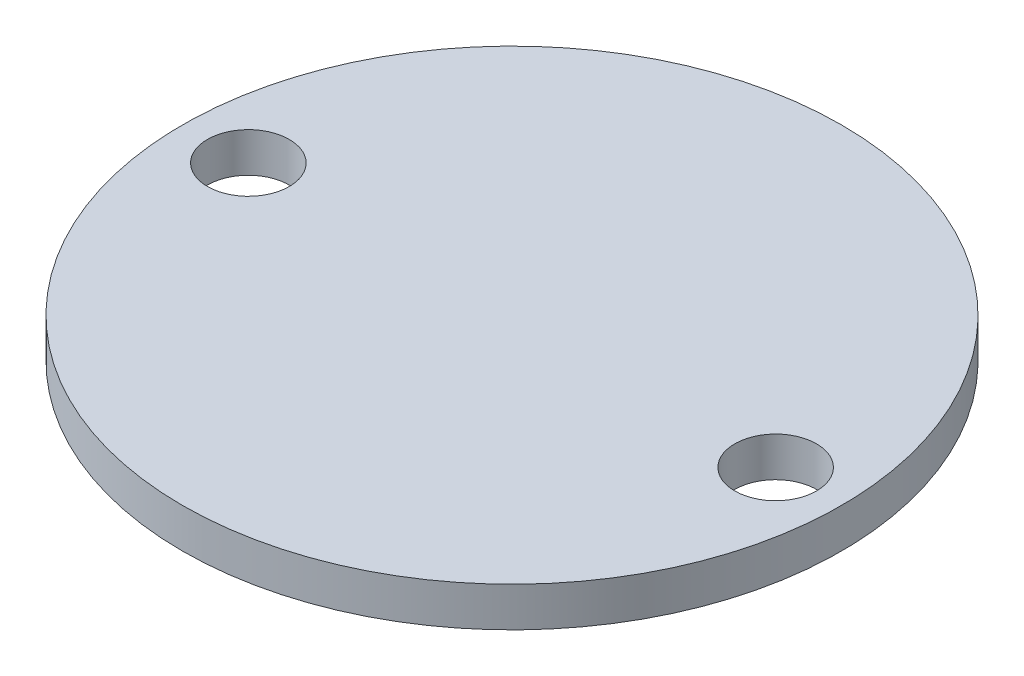
SolidWorks part; units mm, degrees
ref_plane "Спереди" through (0, 0, 0) normal (0, 0, 1) x (1, 0, 0)
ref_plane "Сверху" through (0, 0, 0) normal (0, 1, 0) x (1, 0, 0)
ref_plane "Справа" through (0, 0, 0) normal (1, 0, 0) x (0, 0, -1)
sketch "Эскиз1" plane through (0, 0, 0) normal (0, 1, 0) x (1, 0, 0)
  circle A0 centre (0, 0) radius 12.5
  dimension "D1" = 25
extrude "Бобышка-Вытянуть1" add sketch "Эскиз1" along normal blind 1.5
sketch "Эскиз2" plane through (0, 1.5, 0) normal (0, 1, 0) x (1, 0, 0)
  circle A0 centre (10, 0) radius 1.55
  circle A1 centre (0, 0) radius 10 construction
  circle A2 centre (-10, 0) radius 1.55
  dimension "D1" = 20
  dimension "D2" = 3.1
  dimension "D3" = 3.1
extrude "Вырез-Вытянуть1" cut sketch "Эскиз2" against normal through all
